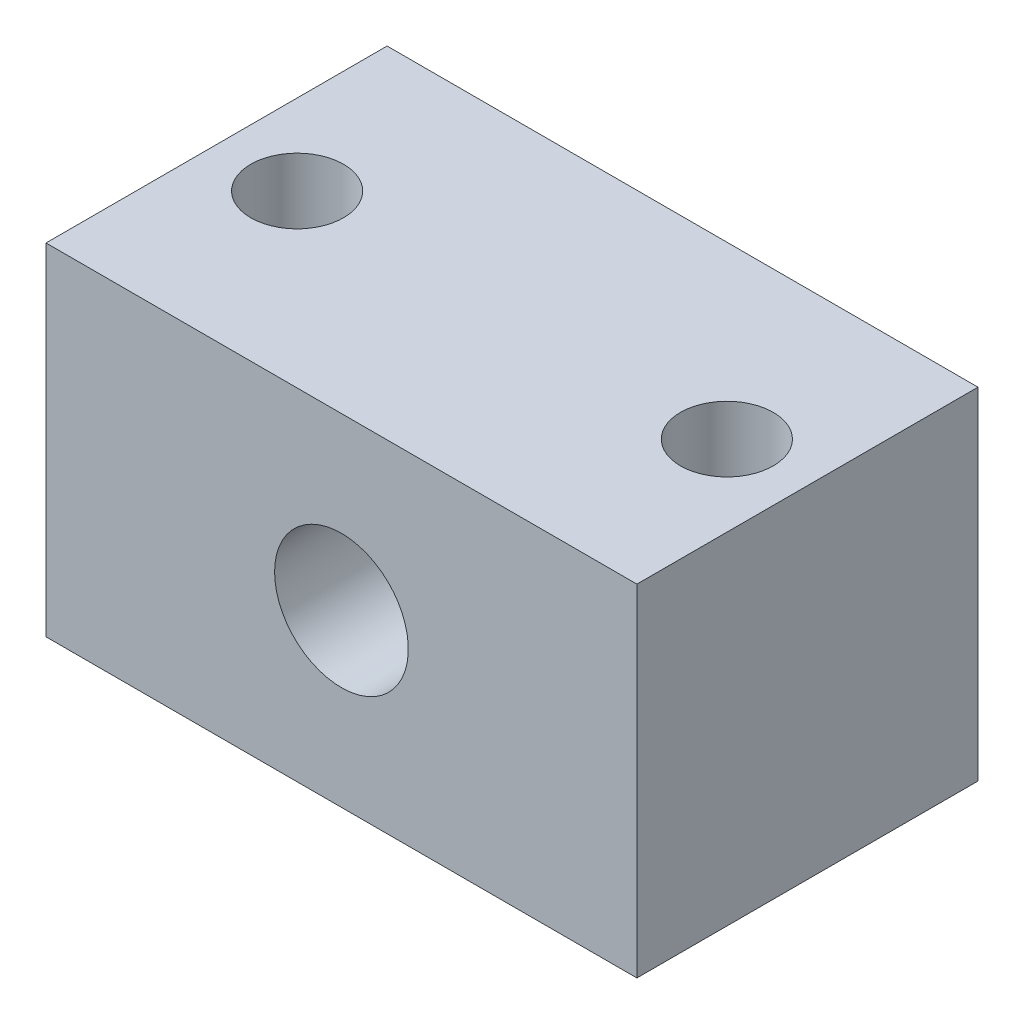
SolidWorks part; units mm, degrees
material "6061-T6 (SS)"
ref_plane "Front Plane" through (0, 0, 0) normal (0, 0, 1) x (1, 0, 0)
ref_plane "Top Plane" through (0, 0, 0) normal (0, 1, 0) x (1, 0, 0)
ref_plane "Right Plane" through (0, 0, 0) normal (1, 0, 0) x (0, 0, -1)
sketch "Sketch1" plane through (0, 0, 0) normal (0, 1, 0) x (1, 0, 0)
  line L0 (22, 12.35) -> (22, 0.35) construction
  line L1 (0, 0) -> (22, 0)
  line L2 (0, 0) -> (0, 12.7)
  line L3 (0, 12.7) -> (22, 12.7)
  line L4 (22, 0) -> (22, 12.7)
  dimension "D1" = 12.7
extrude "Boss-Extrude1" add sketch "Sketch1" along normal mid plane 12.7
hole_wizard "#8-32 Tapped Hole1" positions "3DSketch1" profile "Sketch3" tap size "#8-32" standard "ANSI Inch" end condition through all
sketch3d "3DSketch1"
  line L0 (0, 6.35, -6.35) -> (22, 6.35, -6.35) construction
  line L1 (0, 6.35, -12.7) -> (0, 6.35, 0) construction
  line L2 (22, 6.35, 0) -> (22, 6.35, -12.7) construction
  point P0 (3, 6.35, -6.35)
  point P12 (19, 6.35, -6.35)
  point P13 (0, 0, 0)
  point P14 (18.1302, 6.35, -6.35)
  dimension "D1" = 3
  dimension "D2" = 16
cosmetic thread "Hole Thread1" parameters "D2"=4.1656
sketch "Sketch3" plane through (3, 6.35, -6.35) normal (1, 0, 0) x (0, 0, 1)
  line L0 (0, 0) -> (0, 12.7)
  line L1 (0, 12.7) -> (1.7272, 12.7)
  line L2 (1.7272, 12.7) -> (1.7272, 0)
  line L5 (1.7272, 0) -> (0, 0)
  line L11 (0, -6.35) -> (0, 107.95) construction
  dimension "Thru Tap Drill Dia." = 3.4544
  dimension "Thru Tap Drill Depth" = 12.7
cosmetic thread "Hole Thread2" parameters "D2"=4.1656
sketch "Sketch4" plane through (0, 0, -12.7) normal (0, 0, -1) x (-1, 0, 0)
  line L0 (0, 0) -> (-22, 0) construction
  line L1 (0, 6.35) -> (0, -6.35) construction
  line L2 (-22, 6.35) -> (-22, -6.35) construction
  circle A0 centre (-11, 0) radius 2.4892
  dimension "D1" = 4.9784
extrude "Cut-Extrude1" cut sketch "Sketch4" against normal through all
equation "\"D1@3DSketch1\"=3mm"
